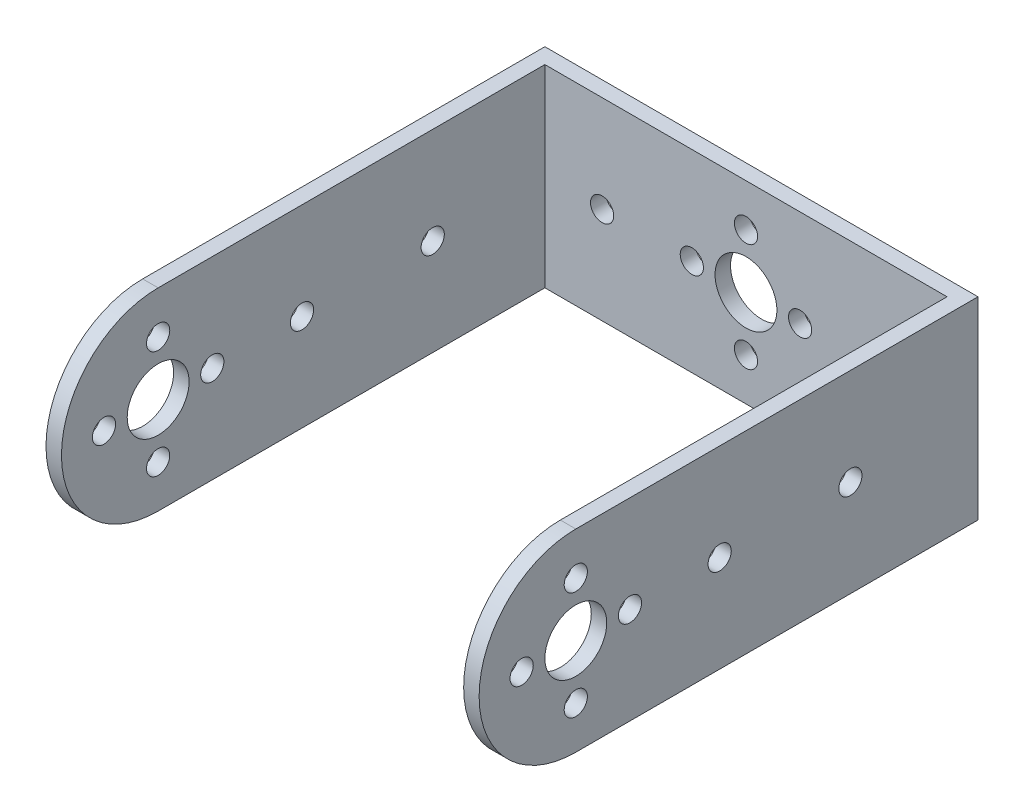
SolidWorks part; units mm, degrees
ref_plane "前视基准面" through (0, 0, 0) normal (0, 0, 1) x (1, 0, 0)
ref_plane "上视基准面" through (0, 0, 0) normal (0, 1, 0) x (1, 0, 0)
ref_plane "右视基准面" through (0, 0, 0) normal (1, 0, 0) x (0, 0, -1)
sketch "草图1" plane through (0, 0, 0) normal (0, 0, 1) x (1, 0, 0)
  line L1 (-28, 12.5) -> (28, 12.5)
  line L2 (-28, 12.5) -> (-28, -12.5)
  line L3 (-28, -12.5) -> (28, -12.5)
  line L4 (28, 12.5) -> (28, -12.5)
  line L5 (-28, 12.5) -> (28, -12.5) construction
  line L6 (-28, -12.5) -> (28, 12.5) construction
  point P0 (0, 0)
  dimension "D1" = 56
  dimension "D2" = 25
extrude "凸台-拉伸1" add sketch "草图1" along normal blind 64.5
sketch "草图2" plane through (0, -12.5, 0) normal (0, -1, 0) x (1, 0, 0)
  line L0 (0, 45.8587) -> (0, -3.5149) construction
  line L1 (-28, 64.5) -> (28, 64.5) construction
  line L2 (0, 64.5) -> (26, 64.5)
  line L3 (26, 64.5) -> (26, 2)
  line L4 (26, 2) -> (-26, 2)
  line L5 (-26, 2) -> (-26, 64.5)
  line L6 (0, 64.5) -> (-26, 64.5)
  point P3 (0, 64.5)
  point P13 (-28, 64.5)
extrude "切除-拉伸1" cut sketch "草图2" against normal through all
sketch "草图3" plane through (28, 0, 0) normal (1, 0, 0) x (0, 0, -1)
  line L0 (-52, 12.5) -> (-64.5, 12.5)
  line L1 (-64.5, 12.5) -> (-64.5, -12.5)
  line L4 (-64.5, -12.5) -> (-52, -12.5)
  line L5 (0, 0) -> (-52, 0) construction
  arc A0 (-52, 12.5) -> (-52, -12.5) centre (-52, 0) ccw
  line M4 (0, 12.5) -> (-64.5, 12.5)
  line M5 (-64.5, 12.5) -> (-64.5, -12.5)
  line M6 (-64.5, -12.5) -> (0, -12.5)
sketch "草图4" plane through (0, 0, 2) normal (0, 0, 1) x (1, 0, 0)
  line L0 (-32.0699, 0) -> (34.4869, 0) construction
  line L1 (0, 16.1115) -> (0, -17.9038) construction
  circle A0 centre (0, 0) radius 4
  circle A1 centre (0, 0) radius 7 construction
  circle A2 centre (0, 7) radius 1.5
  circle A3 centre (0, -7) radius 1.5
  circle A4 centre (-7, 0) radius 1.5
  circle A5 centre (7, 0) radius 1.5
  circle A6 centre (18.6, 0) radius 1.5
  circle A7 centre (-18.6, 0) radius 1.5
  dimension "D1" = 18.6
extrude "切除-拉伸3" cut sketch "草图4" against normal through all
extrude "切除-拉伸4" cut sketch "草图3" against normal through all contours A0 M4 M5 | A0 L1 M6
sketch "草图5" plane through (28, 0, 0) normal (1, 0, 0) x (0, 0, -1)
  line L0 (-52, 0) -> (-33.4, 0) construction
  line L1 (-33.4, 0) -> (-16.5, 0) construction
  circle A0 centre (-52, 0) radius 4
  circle A1 centre (-52, 0) radius 7 construction
  circle A2 centre (-52, 7) radius 1.5
  circle A3 centre (-59, 0) radius 1.5
  circle A4 centre (-52, -7) radius 1.5
  circle A5 centre (-45, 0) radius 1.5
  circle A6 centre (-33.4, 0) radius 1.5
  circle A7 centre (-16.5, 0) radius 1.5
  point P2 (-52, 0)
extrude "切除-拉伸5" cut sketch "草图5" against normal through all
